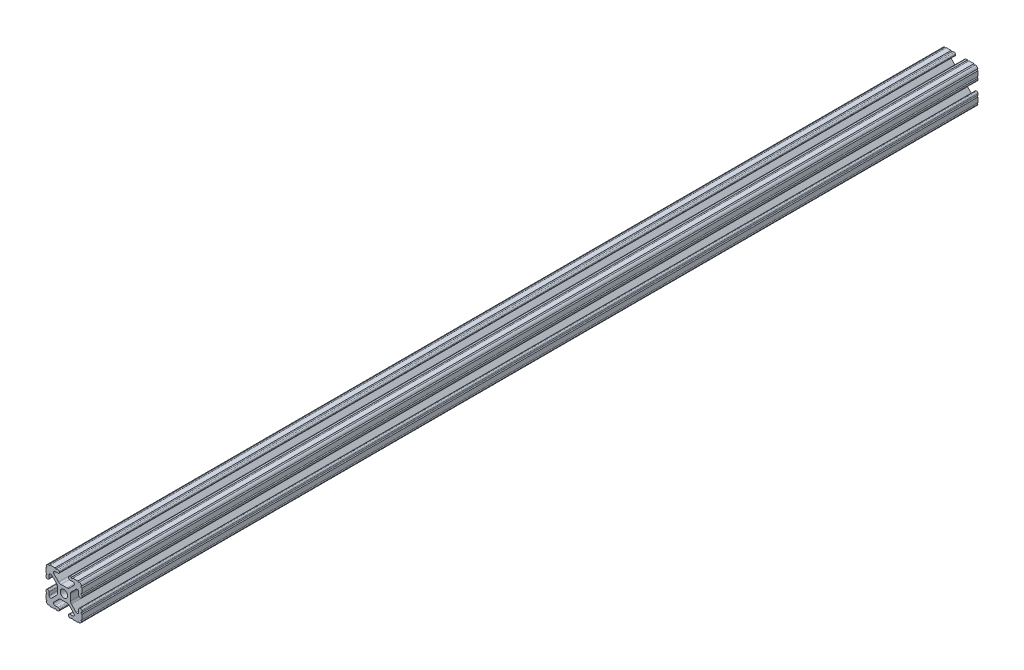
SolidWorks part; units mm, degrees
ref_plane "Front Plane" through (0, 0, 0) normal (0, 0, 1) x (1, 0, 0)
ref_plane "Top Plane" through (0, 0, 0) normal (0, 1, 0) x (1, 0, 0)
ref_plane "Right Plane" through (0, 0, 0) normal (1, 0, 0) x (0, 0, -1)
sketch "Sketch2" plane through (0, 0, 0) normal (0, 0, 1) x (1, 0, 0)
  line L0 (0, 12.7) -> (0, -12.7) construction
  line L1 (-12.7, 0) -> (12.7, 0) construction
  line L2 (3.2512, -12.7) -> (12.7, -12.7)
  line L3 (12.7, -12.7) -> (12.7, -3.2512)
  line L4 (3.2512, -12.7) -> (3.2512, -10.4902)
  line L5 (3.2512, -10.4902) -> (8.9276, -10.4902)
  line L6 (8.9276, -10.4902) -> (3.0856, -4.6482)
  line L7 (0, 0) -> (12.7, -12.7) construction
  line L8 (12.7, -3.2512) -> (10.4902, -3.2512)
  line L9 (10.4902, -3.2512) -> (10.4902, -8.9276)
  line L10 (10.4902, -8.9276) -> (4.6482, -3.0856)
  circle A0 centre (0, 0) radius 2.6035
  arc A1 (6.3485, -10.4902) -> (7.1039, -8.6665) centre (6.3485, -9.4219) ccw construction
  point P8 (0, -4.6482)
  dimension "Center Hole Diameter" = 5.207
  dimension "Rail Height" = 25.4
  dimension "Rail Width" = 25.4
  dimension "T-Slot Width" = 6.5024
  dimension "Slot Inner Width" = 14.8336
  dimension "Thickness" = 2.2098
  dimension "Slot Depth" = 5.842
  dimension "D1" = 2.2098
sketch "Sketch3" plane through (0, 0, 0) normal (1, 0, 0) x (0, 0, -1)
  line L0 (-317.5, -12.7) -> (317.5, -12.7) construction
  line L1 (-292.1, 0) -> (292.1, 0) construction
  dimension "Length" = 635
  dimension "D1" = 25.4
sketch "Sketch4" plane through (0, 0, 0) normal (0, 0, 1) x (1, 0, 0)
  line L0 (4.1904, -12.7) -> (10.1173, -12.7)
  line L1 (3.2512, -12.7) -> (12.7, -12.7) construction
  line L2 (3.2512, -12.7) -> (3.2512, -10.4902) construction
  line L3 (3.2512, -10.4902) -> (8.9276, -10.4902) construction
  line L4 (3.2512, -11.4294) -> (3.2512, -11.7608)
  line L5 (4.1904, -10.4902) -> (6.3485, -10.4902)
  line L6 (0, -4.6482) -> (2.164, -4.6482)
  line L7 (8.9276, -10.4902) -> (3.0856, -4.6482) construction
  line L8 (3.7373, -5.2999) -> (7.1039, -8.6665)
  line L9 (12.7, -12.7) -> (12.7, -3.2512) construction
  line L10 (10.4902, -8.9276) -> (4.6482, -3.0856) construction
  line L11 (10.4902, -3.2512) -> (10.4902, -8.9276) construction
  line L12 (10.4902, -6.3485) -> (10.4902, -4.1904)
  line L13 (12.7, -3.2512) -> (10.4902, -3.2512) construction
  line L14 (11.4294, -3.2512) -> (11.7608, -3.2512)
  line L15 (12.7, -4.1904) -> (12.7, -10.1173)
  line L16 (8.6665, -7.1039) -> (5.2999, -3.7373)
  line L17 (4.6482, 0) -> (4.6482, -2.164)
  line L18 (-12.7, 0) -> (12.7, 0) construction
  line L19 (0, -4.6482) -> (0, -2.6035)
  line L20 (0, 12.7) -> (0, -12.7) construction
  line L21 (4.6482, 0) -> (2.6035, 0)
  arc A0 (3.2512, -11.7608) -> (4.1904, -12.7) centre (4.1904, -11.7608) ccw
  arc A2 (3.2512, -11.4294) -> (4.1904, -10.4902) centre (4.1904, -11.4294) cw
  arc A3 (6.3485, -10.4902) -> (7.1039, -8.6665) centre (6.3485, -9.4219) ccw
  arc A4 (2.164, -4.6482) -> (3.7373, -5.2999) centre (2.164, -6.8732) cw
  arc A5 (10.1173, -12.7) -> (12.7, -10.1173) centre (10.1173, -10.1173) ccw
  arc A6 (8.6665, -7.1039) -> (10.4902, -6.3485) centre (9.4219, -6.3485) ccw
  arc A7 (10.4902, -4.1904) -> (11.4294, -3.2512) centre (11.4294, -4.1904) cw
  arc A8 (11.7608, -3.2512) -> (12.7, -4.1904) centre (11.7608, -4.1904) cw
  arc A9 (5.2999, -3.7373) -> (4.6482, -2.164) centre (6.8732, -2.164) cw
  circle A10 centre (0, 0) radius 2.6035 construction
  arc A11 (0, -2.6035) -> (2.6035, 0) centre (0, 0) ccw
  dimension "D1" = 2.5827
  dimension "D2" = 2.225
  dimension "D3" = 0.9392
extrude "Boss-Extrude1" add sketch "Sketch4" along normal mid plane 635
sketch "Sketch5" plane through (0, 0, 0) normal (0, 0, 1) x (1, 0, 0)
  line L0 (3.2512, -12.7) -> (12.7, -12.7) construction
  line L1 (4.1904, -10.4902) -> (6.3485, -10.4902) construction
  line L3 (0, 0) -> (12.7, -12.7) construction
  line L4 (6.3485, -10.4902) -> (6.3485, -12.7) construction
  line L5 (8.9276, -10.4902) -> (3.0856, -4.6482) construction
  circle A0 centre (10.3562, -12.7) radius 0.5524
  circle A1 centre (5.796, -12.7) radius 0.5524
  circle A2 centre (12.7, -10.3562) radius 0.5524
  circle A3 centre (12.7, -5.796) radius 0.5524
  point P10 (5.2694, -10.4902)
  point P12 (9.4219, -6.3485)
  dimension "D1" = 1.1049
extrude "Cut-Extrude1" cut sketch "Sketch5" against normal through all both and the other way through all
mirror "Mirror1" about plane through (0, 0, 0) normal (1, 0, 0) of bodies 137 134
mirror "Mirror2" about plane through (0, 0, 0) normal (0, 1, 0) of bodies 135
equation "\"D1@Boss-Extrude1\"=\"Length@Sketch3\""
equation "\"D1@Sketch2\"=\"Thickness@Sketch2\""
equation "\"D2@Sketch4\"=\"Slot Inner Width@Sketch2\"*0.15"
equation "\"D1@Sketch4\"=\"D3@Sketch4\"*2.75"
equation "\"D3@Sketch4\"=\"Thickness@Sketch2\"*0.425"
equation "\"D1@Sketch5\"=\"Thickness@Sketch2\"*0.5"
